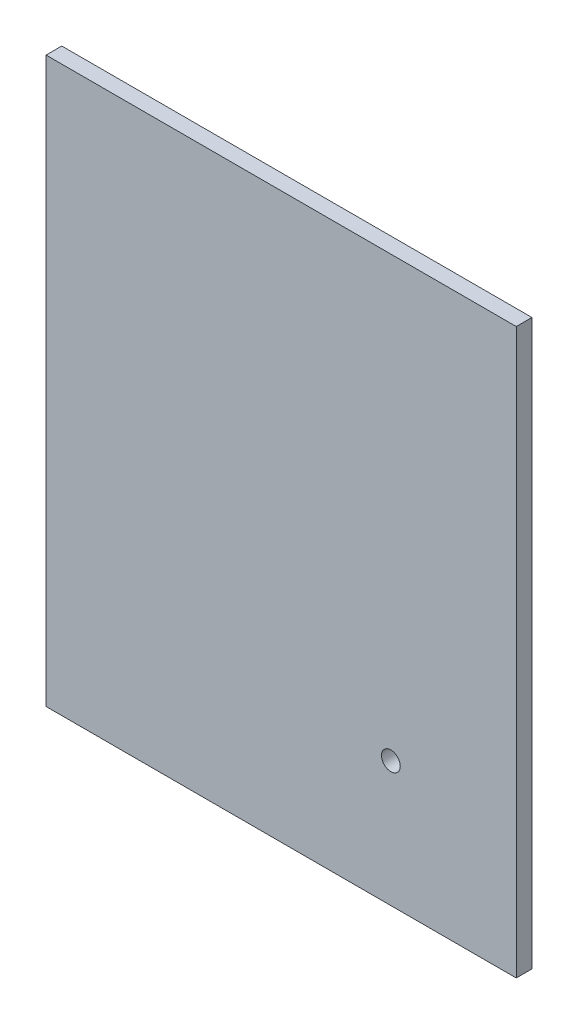
SolidWorks part; units mm, degrees
ref_plane "Front Plane" through (0, 0, 0) normal (0, 0, 1) x (1, 0, 0)
ref_plane "Top Plane" through (0, 0, 0) normal (0, 1, 0) x (1, 0, 0)
ref_plane "Right Plane" through (0, 0, 0) normal (1, 0, 0) x (0, 0, -1)
sketch "Sketch1" plane through (0, 0, 0) normal (0, 0, 1) x (1, 0, 0)
  line L0 (35, -6.0448) -> (35, -133.209) construction
  line L1 (75, -90) -> (-75, -90)
  line L2 (75, -90) -> (75, 90)
  line L3 (75, 90) -> (-75, 90)
  line L4 (-75, -90) -> (-75, 90)
  line L5 (75, -90) -> (-75, 90) construction
  line L6 (75, 90) -> (-75, -90) construction
  line L7 (-105, -50) -> (193.6567, -50)
  circle A0 centre (35, -50) radius 3
  point P0 (0, 0)
  dimension "D5" = 6
  dimension "D1" = 150
  dimension "D2" = 180
  dimension "D3" = 40
  dimension "D4" = 40
extrude "Boss-Extrude1" add sketch "Sketch1" along normal blind 5 contours A0 L7 L2 L3 L4 | A0 L7 L4 L1 L2
